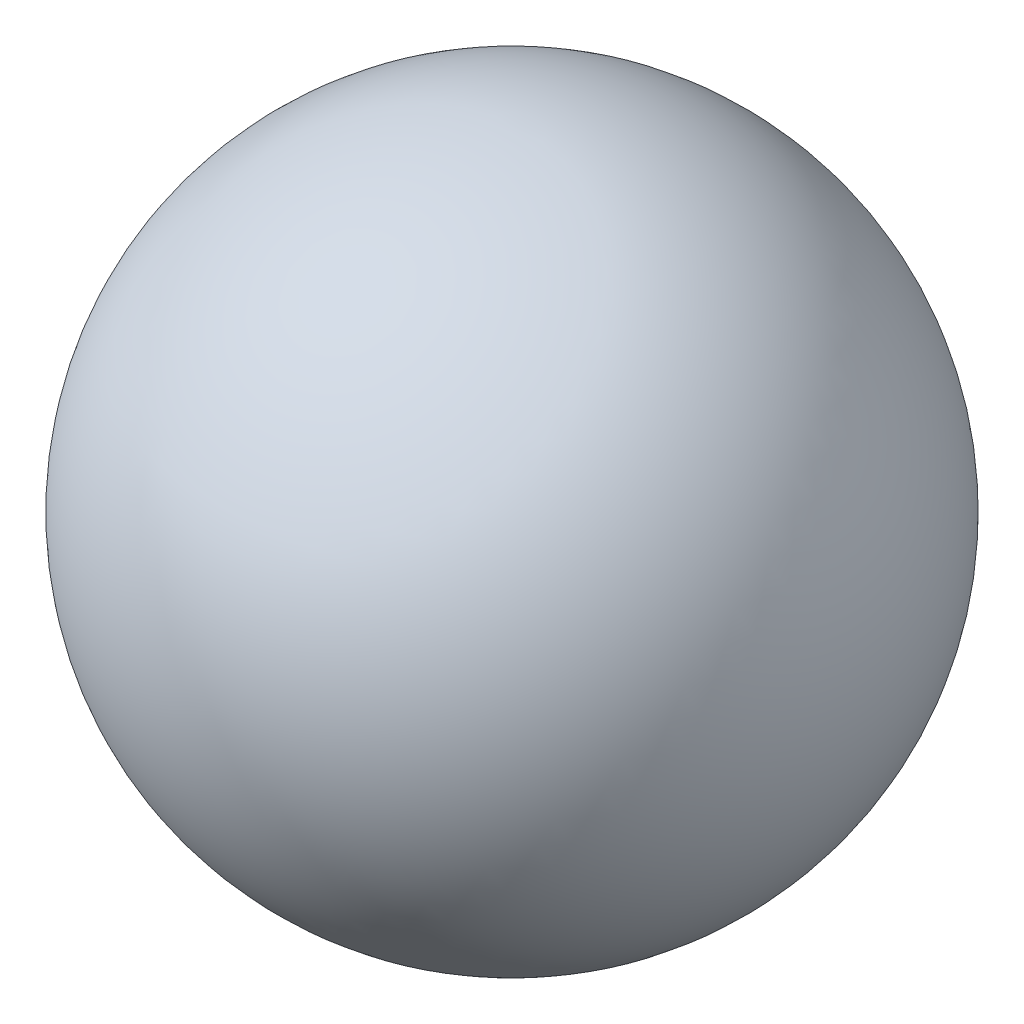
SolidWorks part; units mm, degrees
ref_plane "前视基准面" through (0, 0, 0) normal (0, 0, 1) x (1, 0, 0)
ref_plane "上视基准面" through (0, 0, 0) normal (0, 1, 0) x (1, 0, 0)
ref_plane "右视基准面" through (0, 0, 0) normal (1, 0, 0) x (0, 0, -1)
sketch "Sketch1" plane through (0, 0, 0) normal (0, 0, 1) x (1, 0, 0)
  line L1 (0, -2.25) -> (0, 2.25)
  arc A0 (0, -2.25) -> (0, 2.25) centre (0, 0) cw
  point P6 (0, 0)
revolve "Revolve2" add sketch "Sketch1" angle 360 about L1
